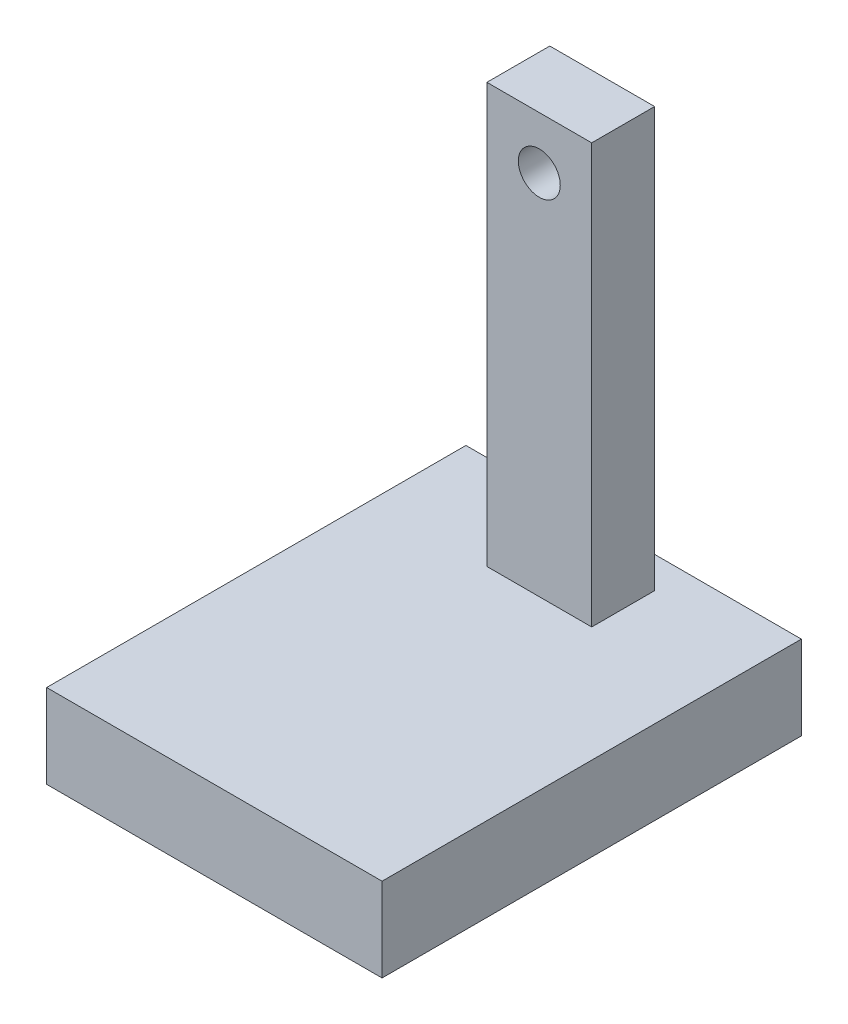
SolidWorks part; units mm, degrees
ref_plane "Front Plane" through (0, 0, 0) normal (0, 0, 1) x (1, 0, 0)
ref_plane "Top Plane" through (0, 0, 0) normal (0, 1, 0) x (1, 0, 0)
ref_plane "Right Plane" through (0, 0, 0) normal (1, 0, 0) x (0, 0, -1)
sketch "Sketch1" plane through (0, 0, 0) normal (0, 1, 0) x (1, 0, 0)
  line L1 (-40, 50) -> (40, 50)
  line L2 (-40, 50) -> (-40, -50)
  line L3 (-40, -50) -> (40, -50)
  line L4 (40, 50) -> (40, -50)
  line L5 (-40, 50) -> (40, -50) construction
  line L6 (-40, -50) -> (40, 50) construction
  point P0 (0, 0)
  dimension "D1" = 80
  dimension "D2" = 100
extrude "Boss-Extrude2" add sketch "Sketch1" along normal blind 20
sketch "Sketch2" plane through (0, 20, 0) normal (0, 1, 0) x (1, 0, 0)
  line L1 (-12.5, 42.5) -> (12.5, 42.5)
  line L2 (-12.5, 42.5) -> (-12.5, 27.5)
  line L3 (-12.5, 27.5) -> (12.5, 27.5)
  line L4 (40, -50) -> (40, 50)
  line L5 (40, 50) -> (-40, 50)
  line L6 (-40, 50) -> (-40, -50)
  line L7 (-40, -50) -> (40, -50)
  line L8 (40, -50) -> (40, 50)
  line L9 (40, 50) -> (-40, 50)
  line L10 (-40, 50) -> (-40, -50)
  line L11 (-40, -50) -> (40, -50)
  line L12 (12.5, 42.5) -> (12.5, 27.5)
  line L13 (-12.5, 42.5) -> (12.5, 27.5) construction
  line L14 (-12.5, 27.5) -> (12.5, 42.5) construction
  point P2 (0, 35)
  dimension "D2" = 25
  dimension "D3" = 15
  dimension "D4" = 40
  dimension "D5" = 15
  dimension "D1" = 0
extrude "Boss-Extrude3" add sketch "Sketch2" along normal blind 100 contours L12 L1 L2 L3
sketch "Sketch3" plane through (0, 0, -27.5) normal (0, 0, 1) x (1, 0, 0)
  line L4 (-12.5, 20) -> (12.5, 20)
  line L5 (12.5, 20) -> (12.5, 120)
  line L6 (12.5, 120) -> (-12.5, 120)
  line L7 (-12.5, 120) -> (-12.5, 20)
  line L8 (-12.5, 20) -> (12.5, 20)
  line L9 (12.5, 20) -> (12.5, 120)
  line L10 (12.5, 120) -> (-12.5, 120)
  line L11 (-12.5, 120) -> (-12.5, 20)
  circle A0 centre (0, 107.5) radius 5
  dimension "D2" = 10
  dimension "D3" = 12.5
  dimension "D4" = 12.5
  dimension "D1" = 0
extrude "Cut-Extrude1" cut sketch "Sketch3" against normal up to next contours A0
sketch "Sketch4" plane through (0, 0, 0) normal (0, -1, 0) x (1, 0, 0)
  line L1 (-35, 45) -> (-15, 45)
  line L2 (-35, 45) -> (-35, 25)
  line L3 (-35, 25) -> (-15, 25)
  line L4 (40, -50) -> (40, 50)
  line L5 (40, 50) -> (-40, 50)
  line L6 (-40, 50) -> (-40, -50)
  line L7 (-40, -50) -> (40, -50)
  line L8 (40, -50) -> (40, 50)
  line L9 (40, 50) -> (-40, 50)
  line L10 (-40, 50) -> (-40, -50)
  line L11 (-40, -50) -> (40, -50)
  line L12 (-15, 45) -> (-15, 25)
  line L13 (-35, 45) -> (-15, 25) construction
  line L14 (-35, 25) -> (-15, 45) construction
  line L19 (0, -55) -> (0, 55) construction
  line L20 (35, -45) -> (15, -45)
  line L25 (15, -25) -> (15, -45)
  line L26 (35, -25) -> (15, -25)
  line L27 (-35, -25) -> (-15, -25)
  line L28 (-35, -25) -> (-35, -45)
  line L29 (-35, -45) -> (-15, -45)
  line L30 (-15, -25) -> (-15, -45)
  line L31 (-35, -25) -> (-15, -45) construction
  line L32 (-35, -45) -> (-15, -25) construction
  line L33 (35, -25) -> (35, -45)
  line L34 (35, 25) -> (15, 25)
  line L35 (15, 45) -> (15, 25)
  line L36 (35, 45) -> (15, 45)
  line L37 (35, 45) -> (35, 25)
  point P2 (-25, 35)
  point P9 (0, 0)
  point P10 (0, 0)
  point P19 (-25, -35)
  point P24 (0, 0)
  point P25 (-25.3397, 35)
  point P27 (-23.1192, 50)
  dimension "D2" = 20
  dimension "D3" = 20
  dimension "D4" = 15
  dimension "D5" = 15
  dimension "D6" = 20
  dimension "D7" = 20
  dimension "D8" = 15
  dimension "D9" = 15
  dimension "D1" = 0
extrude "Boss-Extrude4" add sketch "Sketch4" along normal blind 5 contours L12 L1 L2 L3 | L37 L36 L35 L34 | L33 L26 L25 L20 | L30 L27 L28 L29
